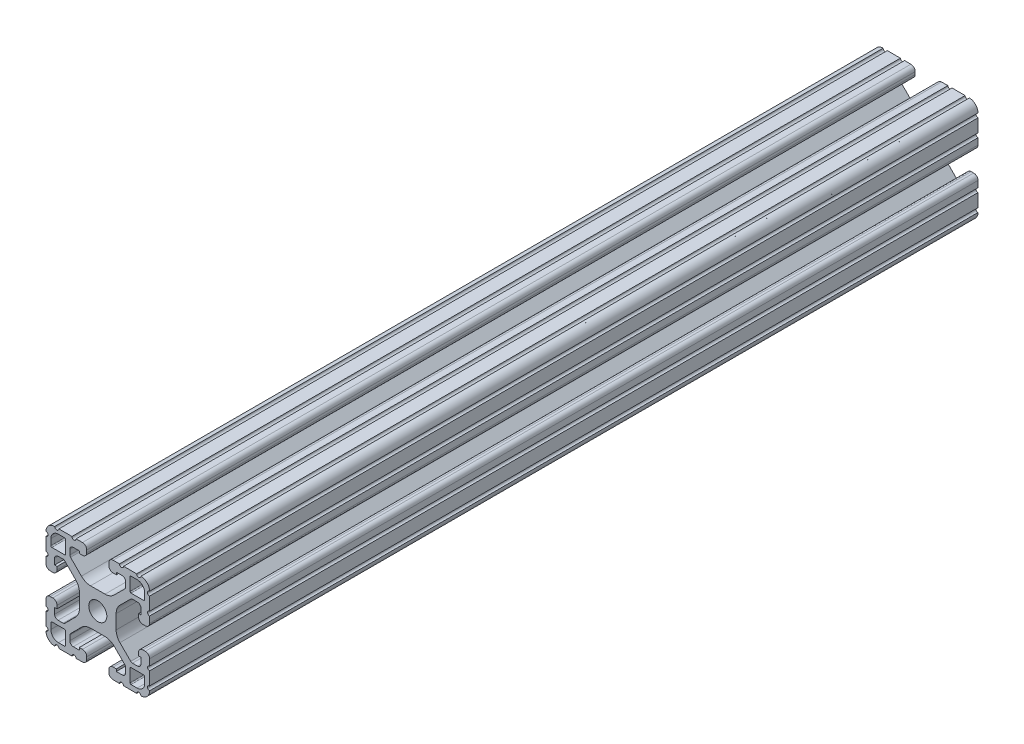
SolidWorks part; units mm, degrees
ref_plane "Front Plane" through (0, 0, 0) normal (0, 0, 1) x (1, 0, 0)
ref_plane "Top Plane" through (0, 0, 0) normal (0, 1, 0) x (1, 0, 0)
ref_plane "Right Plane" through (0, 0, 0) normal (1, 0, 0) x (0, 0, -1)
sketch "Sketch1" plane through (0, 0, 0) normal (0, 0, 1) x (1, 0, 0)
  line L0 (-10.0267, 12.1519) -> (-6.0215, 8.1473)
  line L1 (10.0267, -12.1519) -> (6.0215, -8.1473)
  line L2 (10.287, -14.5547) -> (10.287, -12.7802)
  line L3 (6.8141, -15.8247) -> (9.017, -15.8247)
  line L4 (-10.287, 14.5547) -> (-10.287, 12.7802)
  line L5 (6.8141, -14.986) -> (6.8141, -15.8247)
  line L6 (-6.8141, 15.8247) -> (-9.017, 15.8247)
  line L7 (2.6631, 6.7564) -> (-2.6631, 6.7564)
  line L8 (-6.8141, 14.986) -> (-6.8141, 15.8247)
  line L9 (-5.6388, 14.986) -> (-6.8141, 14.986)
  line L10 (-4.064, 17.4752) -> (-4.064, 16.5608)
  line L11 (-7.9756, 19.05) -> (-5.6388, 19.05)
  line L12 (-14.3256, 19.05) -> (-9.4996, 19.05)
  line L13 (-15.875, 19.05) -> (-15.8496, 19.05)
  line L14 (-19.05, 15.8496) -> (-19.05, 15.875)
  line L15 (-19.05, 9.4996) -> (-19.05, 14.3256)
  line L16 (-19.05, 5.6388) -> (-19.05, 7.9756)
  line L17 (5.6388, -14.986) -> (6.8141, -14.986)
  line L18 (4.064, -17.4752) -> (4.064, -16.5608)
  line L19 (7.9756, -19.05) -> (5.6388, -19.05)
  line L20 (-16.5608, 4.064) -> (-17.4752, 4.064)
  line L21 (14.3256, -19.05) -> (9.4996, -19.05)
  line L22 (-14.986, 6.7506) -> (-14.986, 5.6388)
  line L23 (-15.879, 6.7506) -> (-14.986, 6.7506)
  line L24 (15.875, -19.05) -> (15.8496, -19.05)
  line L25 (19.05, -15.8496) -> (19.05, -15.875)
  line L26 (-15.879, 8.9192) -> (-15.879, 6.7506)
  line L27 (-12.7428, 10.1892) -> (-14.609, 10.1892)
  line L28 (19.05, -9.4996) -> (19.05, -14.3256)
  line L29 (19.05, -5.6388) -> (19.05, -7.9756)
  line L30 (-8.1479, 5.9632) -> (-12.1142, 9.9289)
  line L31 (-16.891, 11.8618) -> (-12.2428, 11.8618)
  line L32 (-11.8618, 12.2428) -> (-11.8618, 16.891)
  line L33 (-12.2428, 17.272) -> (-14.478, 17.272)
  line L34 (-17.272, -14.478) -> (-17.272, -12.2428)
  line L35 (-12.2428, -17.272) -> (-14.478, -17.272)
  line L36 (-11.8618, -12.2428) -> (-11.8618, -16.891)
  line L37 (-16.891, -11.8618) -> (-12.2428, -11.8618)
  line L38 (-17.272, 14.478) -> (-17.272, 12.2428)
  line L39 (16.5608, -4.064) -> (17.4752, -4.064)
  line L40 (14.986, -6.7506) -> (14.986, -5.6388)
  line L41 (15.879, -6.7506) -> (14.986, -6.7506)
  line L42 (15.879, -8.9192) -> (15.879, -6.7506)
  line L43 (12.7428, -10.1892) -> (14.609, -10.1892)
  line L44 (8.1479, -5.9632) -> (12.1142, -9.9289)
  line L45 (6.7564, 2.6043) -> (6.7564, -2.6043)
  line L46 (17.272, 14.478) -> (17.272, 12.2428)
  line L47 (16.891, -11.8618) -> (12.2428, -11.8618)
  line L48 (11.8618, -12.2428) -> (11.8618, -16.891)
  line L49 (12.2428, -17.272) -> (14.478, -17.272)
  line L50 (17.272, -14.478) -> (17.272, -12.2428)
  line L51 (12.2428, 17.272) -> (14.478, 17.272)
  line L52 (11.8618, 12.2428) -> (11.8618, 16.891)
  line L53 (16.891, 11.8618) -> (12.2428, 11.8618)
  line L54 (8.1479, 5.9632) -> (12.1142, 9.9289)
  line L55 (12.7428, 10.1892) -> (14.609, 10.1892)
  line L56 (15.879, 8.9192) -> (15.879, 6.7506)
  line L57 (15.879, 6.7506) -> (14.986, 6.7506)
  line L58 (14.986, 6.7506) -> (14.986, 5.6388)
  line L59 (16.5608, 4.064) -> (17.4752, 4.064)
  line L60 (19.05, 5.6388) -> (19.05, 7.9756)
  line L61 (19.05, 9.4996) -> (19.05, 14.3256)
  line L62 (19.05, 15.8496) -> (19.05, 15.875)
  line L63 (15.875, 19.05) -> (15.8496, 19.05)
  line L64 (14.3256, 19.05) -> (9.4996, 19.05)
  line L65 (7.9756, 19.05) -> (5.6388, 19.05)
  line L66 (4.064, 17.4752) -> (4.064, 16.5608)
  line L67 (5.6388, 14.986) -> (6.8141, 14.986)
  line L68 (6.8141, 14.986) -> (6.8141, 15.8247)
  line L69 (6.8141, 15.8247) -> (9.017, 15.8247)
  line L70 (10.287, 14.5547) -> (10.287, 12.7802)
  line L71 (10.0267, 12.1519) -> (6.0215, 8.1473)
  line L72 (-6.7564, 2.6043) -> (-6.7564, -2.6043)
  line L73 (-8.1479, -5.9632) -> (-12.1142, -9.9289)
  line L74 (-12.7428, -10.1892) -> (-14.609, -10.1892)
  line L75 (-15.879, -8.9192) -> (-15.879, -6.7506)
  line L76 (-15.879, -6.7506) -> (-14.986, -6.7506)
  line L77 (-14.986, -6.7506) -> (-14.986, -5.6388)
  line L78 (-16.5608, -4.064) -> (-17.4752, -4.064)
  line L79 (-19.05, -5.6388) -> (-19.05, -7.9756)
  line L80 (-19.05, -9.4996) -> (-19.05, -14.3256)
  line L81 (-19.05, -15.8496) -> (-19.05, -15.875)
  line L82 (-15.875, -19.05) -> (-15.8496, -19.05)
  line L83 (-14.3256, -19.05) -> (-9.4996, -19.05)
  line L84 (-7.9756, -19.05) -> (-5.6388, -19.05)
  line L85 (-4.064, -17.4752) -> (-4.064, -16.5608)
  line L86 (-5.6388, -14.986) -> (-6.8141, -14.986)
  line L87 (-6.8141, -14.986) -> (-6.8141, -15.8247)
  line L88 (-6.8141, -15.8247) -> (-9.017, -15.8247)
  line L89 (-10.287, -14.5547) -> (-10.287, -12.7802)
  line L90 (-10.0267, -12.1519) -> (-6.0215, -8.1473)
  line L91 (-2.6631, -6.7564) -> (2.6631, -6.7564)
  arc A0 (-10.0267, 12.1519) -> (-10.287, 12.7802) centre (-9.3985, 12.7802) cw
  arc A1 (-19.05, -15.875) -> (-15.875, -19.05) centre (-15.875, -15.875) ccw construction
  arc A2 (-10.287, 14.5547) -> (-9.017, 15.8247) centre (-9.017, 14.5547) cw
  arc A3 (-4.064, 16.5608) -> (-5.6388, 14.986) centre (-5.6388, 16.5608) cw
  arc A4 (10.0267, -12.1519) -> (10.287, -12.7802) centre (9.3985, -12.7802) cw
  arc A5 (10.287, -14.5547) -> (9.017, -15.8247) centre (9.017, -14.5547) cw
  arc A6 (-5.6388, 19.05) -> (-4.064, 17.4752) centre (-5.6388, 17.4752) cw
  arc A7 (-7.9756, 19.05) -> (-9.4996, 19.05) centre (-8.7376, 19.05) cw
  arc A8 (-17.272, -14.478) -> (-14.478, -17.272) centre (-14.478, -14.478) ccw construction
  arc A9 (4.064, -16.5608) -> (5.6388, -14.986) centre (5.6388, -16.5608) cw
  arc A10 (-14.3256, 19.05) -> (-15.8496, 19.05) centre (-15.0876, 19.05) cw
  arc A11 (-19.05, 15.875) -> (-15.875, 19.05) centre (-15.875, 15.875) cw
  arc A12 (-6.0215, 8.1473) -> (-2.6631, 6.7564) centre (-2.6631, 11.5062) ccw
  arc A13 (6.0215, 8.1473) -> (2.6631, 6.7564) centre (2.6631, 11.5062) cw
  arc A14 (-19.05, 15.8496) -> (-19.05, 14.3256) centre (-19.05, 15.0876) cw
  arc A15 (-19.05, 9.4996) -> (-19.05, 7.9756) centre (-19.05, 8.7376) cw
  arc A16 (-17.4752, 4.064) -> (-19.05, 5.6388) centre (-17.4752, 5.6388) cw
  arc A17 (-14.986, 5.6388) -> (-16.5608, 4.064) centre (-16.5608, 5.6388) cw
  arc A18 (-15.879, 8.9192) -> (-14.609, 10.1892) centre (-14.609, 8.9192) cw
  arc A19 (-12.7428, 10.1892) -> (-12.1142, 9.9289) centre (-12.7428, 9.3002) cw
  arc A20 (-16.891, 11.8618) -> (-17.272, 12.2428) centre (-16.891, 12.2428) cw
  arc A21 (5.6388, -19.05) -> (4.064, -17.4752) centre (5.6388, -17.4752) cw
  arc A22 (7.9756, -19.05) -> (9.4996, -19.05) centre (8.7376, -19.05) cw
  arc A23 (14.3256, -19.05) -> (15.8496, -19.05) centre (15.0876, -19.05) cw
  arc A24 (-11.8618, 12.2428) -> (-12.2428, 11.8618) centre (-12.2428, 12.2428) cw
  arc A25 (19.05, -15.875) -> (15.875, -19.05) centre (15.875, -15.875) cw
  arc A26 (-12.2428, 17.272) -> (-11.8618, 16.891) centre (-12.2428, 16.891) cw
  arc A27 (-17.272, 14.478) -> (-14.478, 17.272) centre (-14.478, 14.478) cw
  arc A28 (19.05, -15.8496) -> (19.05, -14.3256) centre (19.05, -15.0876) cw
  arc A29 (19.05, -9.4996) -> (19.05, -7.9756) centre (19.05, -8.7376) cw
  arc A30 (17.4752, -4.064) -> (19.05, -5.6388) centre (17.4752, -5.6388) cw
  arc A31 (14.986, -5.6388) -> (16.5608, -4.064) centre (16.5608, -5.6388) cw
  arc A32 (15.879, -8.9192) -> (14.609, -10.1892) centre (14.609, -8.9192) cw
  arc A33 (12.7428, -10.1892) -> (12.1142, -9.9289) centre (12.7428, -9.3002) cw
  arc A34 (8.1479, -5.9632) -> (6.7564, -2.6043) centre (11.5062, -2.6043) cw
  arc A35 (6.7564, 2.6043) -> (8.1479, 5.9632) centre (11.5062, 2.6043) cw
  arc A36 (16.891, -11.8618) -> (17.272, -12.2428) centre (16.891, -12.2428) cw
  arc A37 (11.8618, -12.2428) -> (12.2428, -11.8618) centre (12.2428, -12.2428) cw
  arc A38 (-17.272, -14.478) -> (-14.478, -17.272) centre (-14.478, -14.478) ccw
  arc A39 (-12.2428, -17.272) -> (-11.8618, -16.891) centre (-12.2428, -16.891) ccw
  arc A40 (-11.8618, -12.2428) -> (-12.2428, -11.8618) centre (-12.2428, -12.2428) ccw
  arc A41 (-16.891, -11.8618) -> (-17.272, -12.2428) centre (-16.891, -12.2428) ccw
  arc A42 (12.2428, -17.272) -> (11.8618, -16.891) centre (12.2428, -16.891) cw
  circle A43 centre (0, 0) radius 3.3274
  arc A44 (17.272, -14.478) -> (14.478, -17.272) centre (14.478, -14.478) cw
  arc A45 (17.272, 14.478) -> (14.478, 17.272) centre (14.478, 14.478) ccw
  arc A46 (12.2428, 17.272) -> (11.8618, 16.891) centre (12.2428, 16.891) ccw
  arc A47 (11.8618, 12.2428) -> (12.2428, 11.8618) centre (12.2428, 12.2428) ccw
  arc A48 (16.891, 11.8618) -> (17.272, 12.2428) centre (16.891, 12.2428) ccw
  arc A49 (12.7428, 10.1892) -> (12.1142, 9.9289) centre (12.7428, 9.3002) ccw
  arc A50 (15.879, 8.9192) -> (14.609, 10.1892) centre (14.609, 8.9192) ccw
  arc A51 (14.986, 5.6388) -> (16.5608, 4.064) centre (16.5608, 5.6388) ccw
  arc A52 (17.4752, 4.064) -> (19.05, 5.6388) centre (17.4752, 5.6388) ccw
  arc A53 (19.05, 9.4996) -> (19.05, 7.9756) centre (19.05, 8.7376) ccw
  arc A54 (19.05, 15.8496) -> (19.05, 14.3256) centre (19.05, 15.0876) ccw
  arc A55 (19.05, 15.875) -> (15.875, 19.05) centre (15.875, 15.875) ccw
  arc A56 (14.3256, 19.05) -> (15.8496, 19.05) centre (15.0876, 19.05) ccw
  arc A57 (7.9756, 19.05) -> (9.4996, 19.05) centre (8.7376, 19.05) ccw
  arc A58 (5.6388, 19.05) -> (4.064, 17.4752) centre (5.6388, 17.4752) ccw
  arc A59 (4.064, 16.5608) -> (5.6388, 14.986) centre (5.6388, 16.5608) ccw
  arc A60 (10.287, 14.5547) -> (9.017, 15.8247) centre (9.017, 14.5547) ccw
  arc A61 (10.0267, 12.1519) -> (10.287, 12.7802) centre (9.3985, 12.7802) ccw
  arc A62 (-6.7564, 2.6043) -> (-8.1479, 5.9632) centre (-11.5062, 2.6043) ccw
  arc A63 (-8.1479, -5.9632) -> (-6.7564, -2.6043) centre (-11.5062, -2.6043) ccw
  arc A64 (-12.7428, -10.1892) -> (-12.1142, -9.9289) centre (-12.7428, -9.3002) ccw
  arc A65 (-15.879, -8.9192) -> (-14.609, -10.1892) centre (-14.609, -8.9192) ccw
  arc A66 (-14.986, -5.6388) -> (-16.5608, -4.064) centre (-16.5608, -5.6388) ccw
  arc A67 (-17.4752, -4.064) -> (-19.05, -5.6388) centre (-17.4752, -5.6388) ccw
  arc A68 (-19.05, -9.4996) -> (-19.05, -7.9756) centre (-19.05, -8.7376) ccw
  arc A69 (-19.05, -15.8496) -> (-19.05, -14.3256) centre (-19.05, -15.0876) ccw
  arc A70 (-19.05, -15.875) -> (-15.875, -19.05) centre (-15.875, -15.875) ccw
  arc A71 (-14.3256, -19.05) -> (-15.8496, -19.05) centre (-15.0876, -19.05) ccw
  arc A72 (-7.9756, -19.05) -> (-9.4996, -19.05) centre (-8.7376, -19.05) ccw
  arc A73 (-5.6388, -19.05) -> (-4.064, -17.4752) centre (-5.6388, -17.4752) ccw
  arc A74 (-4.064, -16.5608) -> (-5.6388, -14.986) centre (-5.6388, -16.5608) ccw
  arc A75 (-10.287, -14.5547) -> (-9.017, -15.8247) centre (-9.017, -14.5547) ccw
  arc A76 (-10.0267, -12.1519) -> (-10.287, -12.7802) centre (-9.3985, -12.7802) ccw
  arc A77 (-2.6631, -6.7564) -> (-6.0215, -8.1473) centre (-2.6631, -11.5062) ccw
  arc A78 (6.0215, -8.1473) -> (2.6631, -6.7564) centre (2.6631, -11.5062) ccw
  point P134 (0, 0)
extrude "Boss-Extrude1" add sketch "Sketch1" along normal mid plane 304.8
